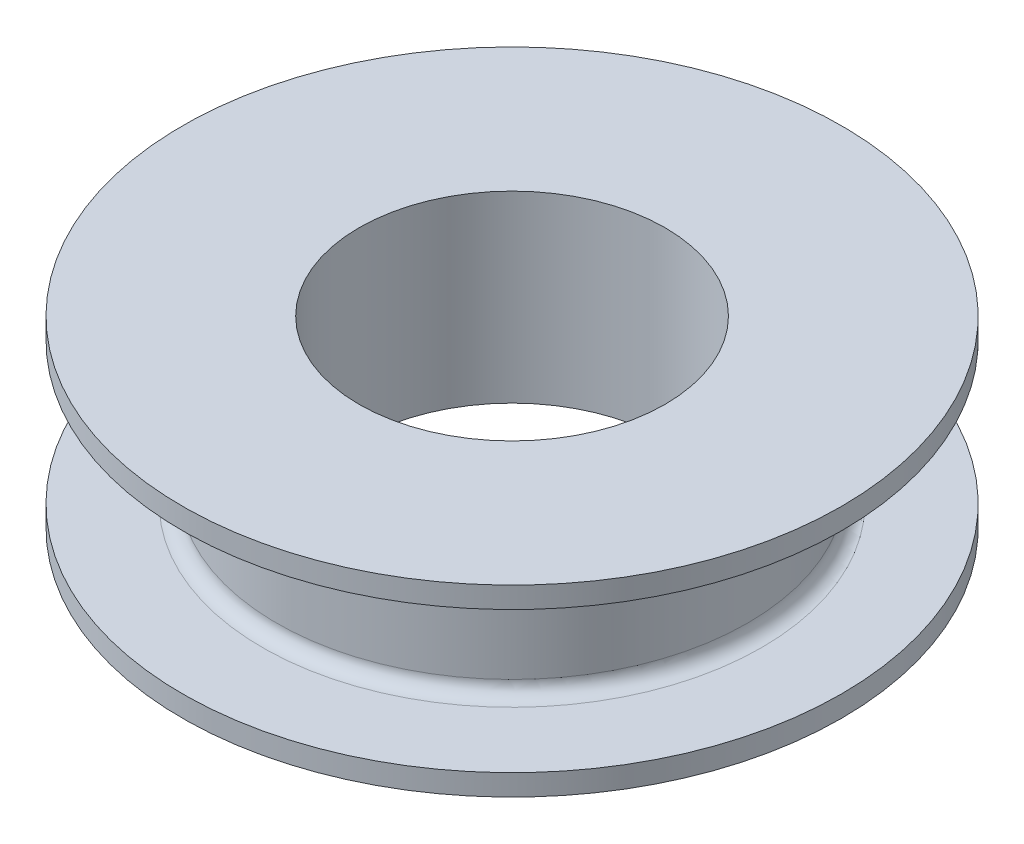
SolidWorks part; units mm, degrees
ref_plane "正面" through (0, 0, 0) normal (0, 0, 1) x (1, 0, 0)
ref_plane "平面" through (0, 0, 0) normal (0, 1, 0) x (1, 0, 0)
ref_plane "右側面" through (0, 0, 0) normal (1, 0, 0) x (0, 0, -1)
sketch "ｽｹｯﾁ1" plane through (0, 0, 0) normal (0, 0, 1) x (1, 0, 0)
  line L0 (7, 3.45) -> (5.3, 3.45)
  line L1 (3.25, 0) -> (7, 0)
  line L2 (0, 0) -> (0, 1.95) construction
  line L3 (3.25, 3.9) -> (7, 3.9)
  line L4 (7, 0) -> (7, 0.45)
  line L5 (5, 3.15) -> (5, 0.75)
  line L6 (5, 1.95) -> (0, 1.95) construction
  line L7 (3.25, 3.9) -> (3.25, 0)
  line L8 (0, 3.9) -> (3.25, 3.9) construction
  line L9 (0, 1.95) -> (0, 3.9) construction
  line L10 (0, 0) -> (3.25, 0) construction
  line L11 (7, 0.45) -> (5.3, 0.45)
  line L12 (7, 3.45) -> (7, 3.9)
  line L13 (7, 0.45) -> (7, 3.45) construction
  arc A0 (5.3, 0.45) -> (5, 0.75) centre (5.3, 0.75) cw
  arc A1 (5.3, 3.45) -> (5, 3.15) centre (5.3, 3.15) ccw
  point P13 (0, 0)
  point P14 (8.2008, 3.45)
  point P17 (5, 0.45)
  point P20 (5, 3.45)
  dimension "D6" = 0.3
  dimension "D1" = 6.5
  dimension "D2" = 10
  dimension "D3" = 3.9
  dimension "D4" = 3
  dimension "D5" = 2
revolve "回転1" add sketch "ｽｹｯﾁ1" angle 360 about L9
